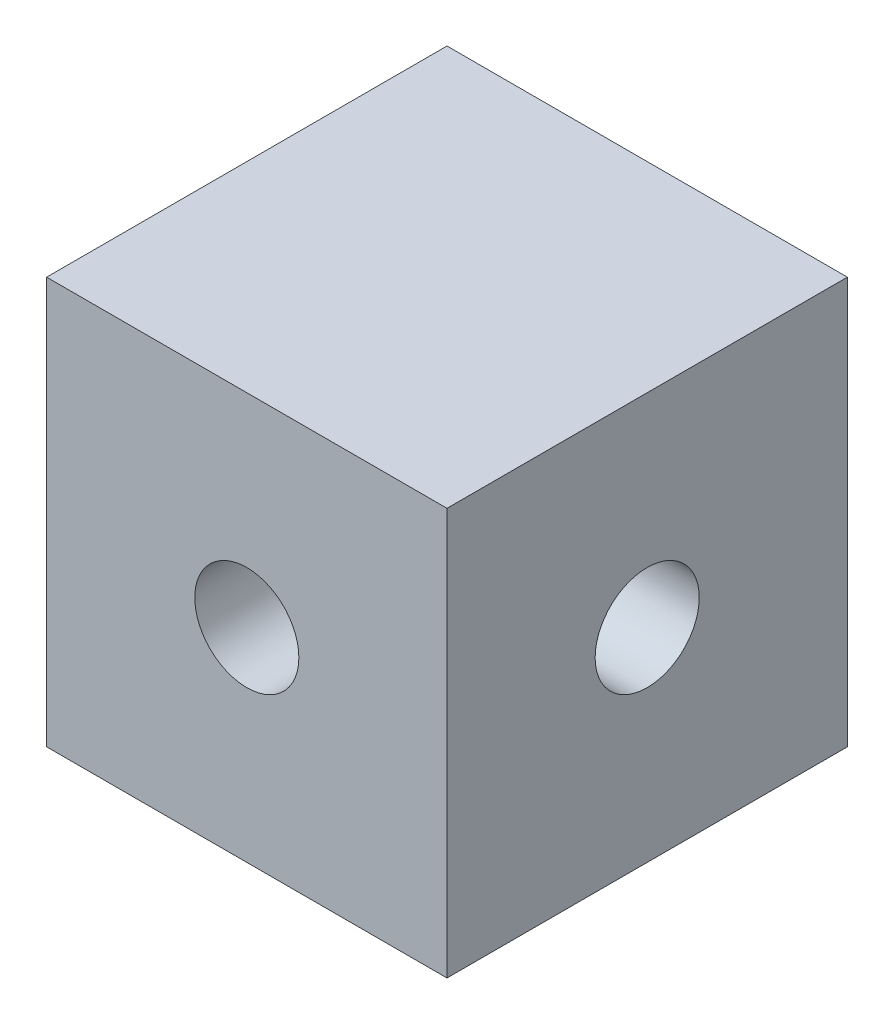
SolidWorks part; units mm, degrees
ref_plane "Front Plane" through (0, 0, 0) normal (0, 0, 1) x (1, 0, 0)
ref_plane "Top Plane" through (0, 0, 0) normal (0, 1, 0) x (1, 0, 0)
ref_plane "Right Plane" through (0, 0, 0) normal (1, 0, 0) x (0, 0, -1)
sketch "Sketch2" plane through (0, 0, 0) normal (0, 1, 0) x (1, 0, 0)
  line L1 (-10, 10) -> (10, 10)
  line L2 (-10, 10) -> (-10, -10)
  line L3 (-10, -10) -> (10, -10)
  line L4 (10, 10) -> (10, -10)
  line L5 (-10, 10) -> (10, -10) construction
  line L6 (-10, -10) -> (10, 10) construction
  point P0 (0, 0)
  dimension "D1" = 20
  dimension "D2" = 20
extrude "Boss-Extrude1" add sketch "Sketch2" along normal blind 20.32
sketch "Sketch3" plane through (0, 0, 10) normal (0, 0, 1) x (1, 0, 0)
  line L0 (0, 20.32) -> (0, 0) construction
  line L1 (-10, 20.32) -> (10, 20.32) construction
  circle A0 centre (0, 10.16) radius 2.6
  dimension "D1" = 5.2
extrude "Cut-Extrude1" cut sketch "Sketch3" against normal blind 10.16 contours A0
sketch "Sketch4" plane through (0, 0, 0) normal (0, 0, 1) x (1, 0, 0)
  line L0 (0, 20.32) -> (0, 0) construction
  line L1 (-10, 20.32) -> (10, 20.32) construction
pattern_circular "CirPattern1" count 4 over 360 about axis through (0, 20.32, 0) along (0, -1, 0) of "Cut-Extrude1"
